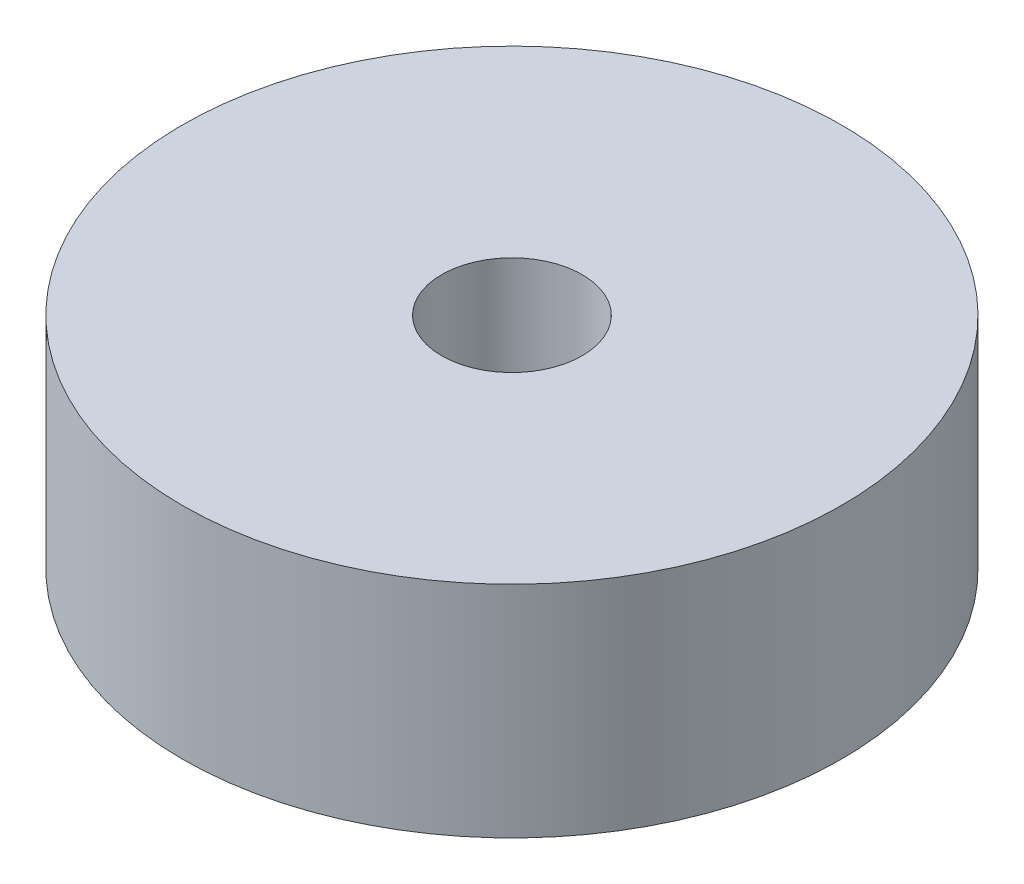
SolidWorks part; units mm, degrees
ref_plane "正面" through (0, 0, 0) normal (0, 0, 1) x (1, 0, 0)
ref_plane "平面" through (0, 0, 0) normal (0, 1, 0) x (1, 0, 0)
ref_plane "右側面" through (0, 0, 0) normal (1, 0, 0) x (0, 0, -1)
sketch "ｽｹｯﾁ1" plane through (0, 0, 0) normal (0, 1, 0) x (1, 0, 0)
  circle A0 centre (0, 0) radius 1.6
  circle A1 centre (0, 0) radius 7.5
  dimension "D1" = 3.2
  dimension "D2" = 15
extrude "ﾎﾞｽ - 押し出し1" add sketch "ｽｹｯﾁ1" along normal blind 5
